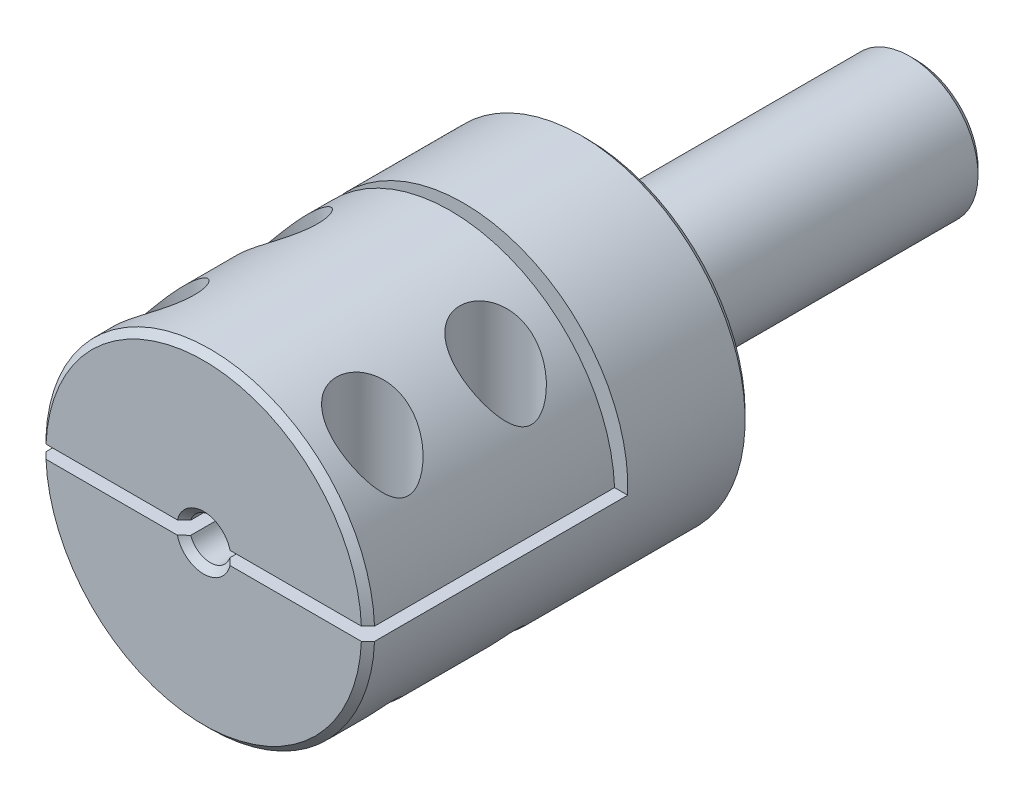
SolidWorks part; units mm, degrees
ref_plane "Front" through (0, 0, 0) normal (0, 0, 1) x (1, 0, 0)
ref_plane "Top" through (0, 0, 0) normal (0, 1, 0) x (1, 0, 0)
ref_plane "Right" through (0, 0, 0) normal (1, 0, 0) x (0, 0, -1)
sketch "Sketch1" plane through (0, 0, 0) normal (1, 0, 0) x (0, 0, -1)
  line L0 (-41.275, 19.05) -> (3.175, 19.05)
  line L1 (3.175, 19.05) -> (3.175, 7.9375)
  line L2 (3.175, 7.9375) -> (41.275, 7.9375)
  line L3 (41.275, 7.9375) -> (41.275, 0)
  line L4 (41.275, 0) -> (-4.9192, 0)
  line L6 (-41.275, 2.3812) -> (-41.275, 19.05)
  line L7 (41.275, 7.9375) -> (41.275, -7.9375) construction
  line L8 (-41.275, 2.3812) -> (-6.35, 2.3812)
  line L9 (-6.35, 2.3812) -> (-4.9192, 0)
  line L10 (-41.275, 19.05) -> (-41.275, -19.05) construction
  line L11 (-41.275, 0) -> (41.275, 0) construction
  line L12 (-4.9192, 0) -> (-6.35, -2.3812) construction
  line L13 (-6.35, 2.3812) -> (-6.35, -2.3812) construction
  line L14 (-6.35, -2.3812) -> (-41.275, -2.3812) construction
  point P12 (-6.35, 0)
  dimension "D1" = 121
revolve "Revolve1" add sketch "Sketch1" angle 360 mid plane about L4
ref_plane "Plane1" through (0, 0, 34.1312) normal (0, 0, 1) x (1, 0, 0)
sketch "Sketch4" plane through (0, 0, 34.1312) normal (0, 0, 1) x (1, 0, 0)
  line L0 (14.8082, 4.3434) -> (16.3576, 4.3434)
  line L1 (14.8082, 4.3434) -> (14.8082, -19.05)
  line L2 (14.8082, -19.05) -> (12.3952, -19.05)
  line L3 (12.3952, -19.05) -> (12.3952, 19.05)
  line L4 (12.3952, 19.05) -> (16.3576, 19.05)
  line L5 (16.3576, 19.05) -> (16.3576, 9.1694)
  line L6 (16.3576, 9.1694) -> (16.3576, 4.3434)
  line L7 (16.3576, 9.1694) -> (12.3952, 9.1694) construction
  line L8 (16.3576, 19.05) -> (8.4328, 19.05) construction
  line L9 (14.8082, -19.05) -> (9.9822, -19.05) construction
revolve "Cut-Revolve1" cut sketch "Sketch4" angle 360 mid plane about L3
sketch "Sketch5" plane through (0, 0, 34.1312) normal (0, 0, 1) x (1, 0, 0)
  line L0 (12.3952, -19.05) -> (12.3952, 19.05) construction
  line L1 (14.8082, 4.3434) -> (14.8082, -19.05) construction
  line L2 (14.8082, 4.3434) -> (16.3576, 4.3434) construction
  line L3 (16.3576, 9.1694) -> (16.3576, 4.3434) construction
  line L4 (16.3576, 9.1694) -> (12.3952, 9.1694) construction
  line L5 (12.3952, -11.5316) -> (12.3952, 9.1694)
  line L6 (14.8082, 4.3434) -> (14.8082, -11.5316)
  line L7 (14.8082, 4.3434) -> (16.3576, 4.3434)
  line L8 (16.3576, 9.1694) -> (16.3576, 4.3434)
  line L9 (16.3576, 9.1694) -> (12.3952, 9.1694)
  line L10 (12.3952, -11.5316) -> (14.8082, -11.5316)
  dimension "screw length" = 15.875
sketch "Sketch11" plane through (0, 4.3434, 0) normal (0, 1, 0) x (1, 0, 0)
  circle A3 centre (12.3952, -34.1312) radius 4.1605
  dimension ".328" = 8.321
extrude "Cut-Extrude4" cut sketch "Sketch11" along normal through all
pattern_linear "LPattern1" count 2 spacing 14.2875 along (0, 0, -1) count 2 spacing 24.7904 along (-1, 0, 0) of "Cut-Extrude4", "Cut-Revolve1"
chamfer "Chamfer1" distance 0.762 angle 45 4 edges at (0, 2.3812, 41.275) (0, 19.05, 41.275) (0, 7.9375, -41.275) (0, 19.05, -3.175)
fillet "Fillet1" radius 0.762 1 edges at (0, 7.9375, -3.175)
sketch "Sketch14" plane through (0, 0, 0) normal (1, 0, 0) x (0, 0, -1)
  line L0 (-41.275, 19.05) -> (3.175, 19.05) construction
  line L1 (-41.275, 0.762) -> (-12.7, 0.762)
  line L2 (-41.275, 0.762) -> (-41.275, -0.762)
  line L3 (-41.275, -0.762) -> (-11.176, -0.762)
  line L4 (-12.7, 19.05) -> (-19.8437, 19.05) construction
  line L5 (-12.7, 19.05) -> (-11.176, 19.05)
  line L6 (-12.7, 19.05) -> (-12.7, 0.762)
  line L7 (-19.8437, 13.6722) -> (-19.8437, 4.3434) construction
  line L8 (-11.176, 19.05) -> (-11.176, -0.762)
  dimension "D1" = 1.524
  dimension "D2" = 7.1437
extrude "Cut-Extrude6" cut sketch "Sketch14" against normal through all and the other way through all
equation "\"D1@Chamfer1\" = \"OD@Sketch1\" * .02"
equation "\".328@Sketch11\" = \"screw head dia@Sketch4\" * 1.05"
equation "\"D4@LPattern1\" = \"screw offset 2@Sketch4\" * 2"
equation "\"D2@Sketch14\" = \"screw offset@Plane1\""
